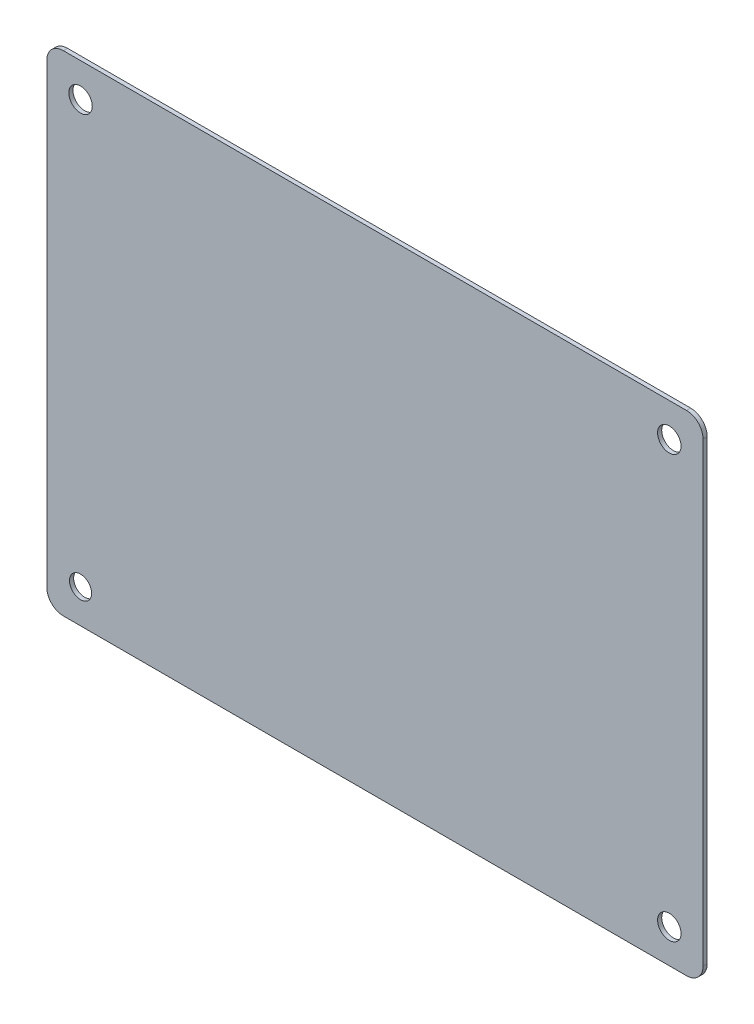
SolidWorks part; units mm, degrees
ref_plane "Front Plane" through (0, 0, 0) normal (0, 0, 1) x (1, 0, 0)
ref_plane "Top Plane" through (0, 0, 0) normal (0, 1, 0) x (1, 0, 0)
ref_plane "Right Plane" through (0, 0, 0) normal (1, 0, 0) x (0, 0, -1)
sketch "Sketch1" plane through (0, 0, 0) normal (0, 0, 1) x (1, 0, 0)
  line L9 (403.9185, 1238.2916) -> (643.1399, 1238.2916)
  line L10 (397.5685, 1244.6416) -> (397.5685, 1419.863)
  line L11 (403.9185, 1426.213) -> (643.1399, 1426.213)
  line L12 (649.4899, 1244.6416) -> (649.4899, 1419.863)
  circle A2 centre (410.5292, 1413.2523) radius 4.5
  circle A3 centre (636.5292, 1413.2523) radius 4.5
  circle A4 centre (636.5292, 1251.2523) radius 4.5
  circle A5 centre (410.5292, 1251.2523) radius 4.25
  arc A10 (649.0292, 1416.6772) -> (636.5292, 1426.213) centre (636.5292, 1413.2523) ccw construction
  arc A11 (403.9185, 1238.2916) -> (397.5685, 1244.6416) centre (403.9185, 1244.6416) cw
  arc A12 (643.1399, 1238.2916) -> (649.4899, 1244.6416) centre (643.1399, 1244.6416) ccw
  arc A13 (643.1399, 1426.213) -> (649.4899, 1419.863) centre (643.1399, 1419.863) cw
  arc A14 (397.5685, 1419.863) -> (403.9185, 1426.213) centre (403.9185, 1419.863) cw
  arc A15 (636.5292, 1238.2916) -> (648.7079, 1246.8183) centre (636.5292, 1251.2523) ccw construction
  dimension "D1" = 9
  dimension "D2" = 6.35
extrude "Boss-Extrude1" add sketch "Sketch1" along normal blind 1.5875
